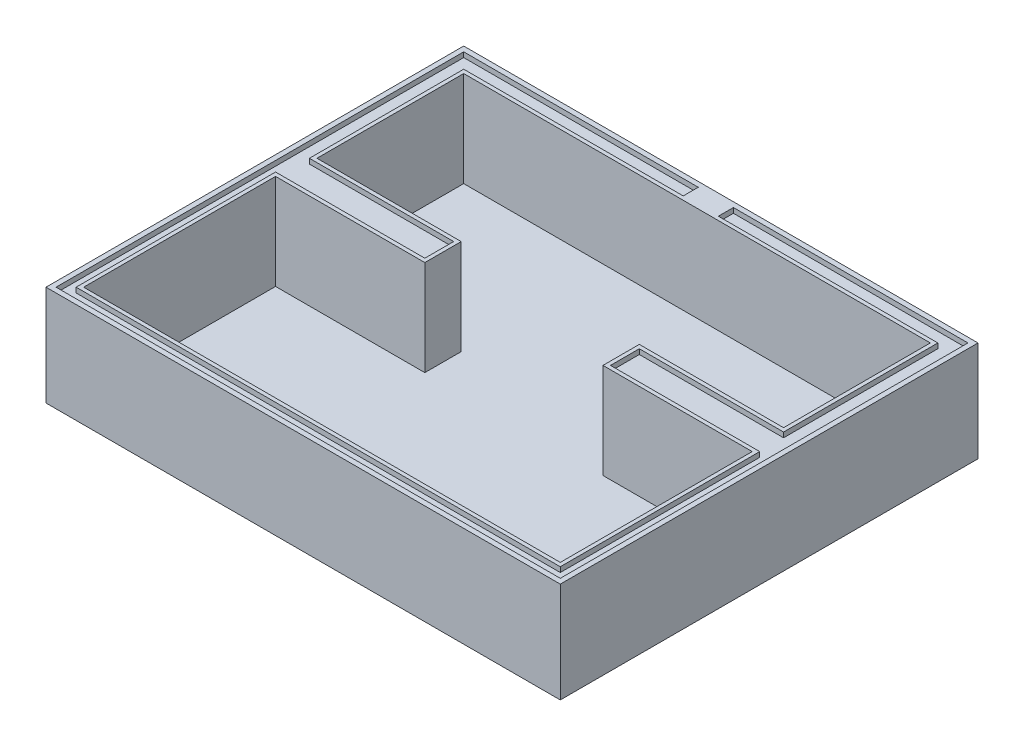
SolidWorks part; units mm, degrees
ref_plane "Front Plane" through (0, 0, 0) normal (0, 0, 1) x (1, 0, 0)
ref_plane "Top Plane" through (0, 0, 0) normal (0, 1, 0) x (1, 0, 0)
ref_plane "Right Plane" through (0, 0, 0) normal (1, 0, 0) x (0, 0, -1)
sketch "Sketch1" plane through (0, 0, 0) normal (0, 1, 0) x (1, 0, 0)
  line L1 (102.5, 83.25) -> (-102.5, 83.25)
  line L2 (102.5, 83.25) -> (102.5, -83.25)
  line L3 (102.5, -83.25) -> (-102.5, -83.25)
  line L4 (-102.5, 83.25) -> (-102.5, -83.25)
  line L5 (102.5, 83.25) -> (-102.5, -83.25) construction
  line L6 (102.5, -83.25) -> (-102.5, 83.25) construction
  point P0 (0, 0)
  dimension "D1" = 166.5
  dimension "D2" = 205
extrude "Boss-Extrude1" add sketch "Sketch1" along normal mid plane 40
sketch "Sketch3" plane through (0, 20, 0) normal (0, 1, 0) x (1, 0, 0)
  line L0 (-37.5, 13.25) -> (-37.5, 5.75) construction
  line L1 (-37.5, 5.75) -> (-100, 5.75) construction
  line L2 (-100, 5.75) -> (-100, 80.75) construction
  line L3 (-100, 80.75) -> (-7.5, 80.75) construction
  line L4 (-7.5, 80.75) -> (-7.5, 75.75) construction
  line L5 (-7.5, 75.75) -> (-95, 75.75) construction
  line L6 (-95, 75.75) -> (-95, 13.25) construction
  line L7 (-95, 13.25) -> (-37.5, 13.25) construction
  line L8 (-100, 5.75) -> (-37.5, 5.75) construction
  line L9 (-37.5, 5.75) -> (-37.5, 2.75) construction
  line L10 (-37.5, 2.75) -> (-97, 2.75) construction
  line L11 (-97, 2.75) -> (-97, -77.75) construction
  line L12 (-97, -77.75) -> (97, -77.75) construction
  line L13 (97, -77.75) -> (97, 2.75) construction
  line L14 (97, 2.75) -> (37.5, 2.75) construction
  line L15 (37.5, 2.75) -> (37.5, 5.75) construction
  line L16 (37.5, 5.75) -> (100, 5.75) construction
  line L17 (100, 5.75) -> (100, -80.75) construction
  line L18 (100, -80.75) -> (-100, -80.75) construction
  line L19 (-100, -80.75) -> (-100, 5.75) construction
  line L20 (37.5, 5.75) -> (37.5, 13.25) construction
  line L21 (37.5, 13.25) -> (95, 13.25) construction
  line L22 (95, 13.25) -> (95, 75.75) construction
  line L23 (95, 75.75) -> (7.5, 75.75) construction
  line L24 (7.5, 75.75) -> (7.5, 80.75) construction
  line L25 (7.5, 80.75) -> (100, 80.75) construction
  line L26 (100, 80.75) -> (100, 5.75) construction
  line L27 (100, 5.75) -> (37.5, 5.75) construction
  line L28 (-37.5, 13.25) -> (-37.5, 5.75)
  line L29 (-37.5, 5.75) -> (-100, 5.75)
  line L30 (-100, 5.75) -> (-100, 80.75)
  line L31 (-100, 80.75) -> (-7.5, 80.75)
  line L32 (-7.5, 80.75) -> (-7.5, 75.75)
  line L33 (-7.5, 75.75) -> (-95, 75.75)
  line L34 (-95, 75.75) -> (-95, 13.25)
  line L35 (-95, 13.25) -> (-37.5, 13.25)
  line L36 (-100, 5.75) -> (-37.5, 5.75)
  line L37 (-37.5, 5.75) -> (-37.5, 2.75)
  line L38 (-37.5, 2.75) -> (-97, 2.75)
  line L39 (-97, 2.75) -> (-97, -77.75)
  line L40 (-97, -77.75) -> (97, -77.75)
  line L41 (97, -77.75) -> (97, 2.75)
  line L42 (97, 2.75) -> (37.5, 2.75)
  line L43 (37.5, 2.75) -> (37.5, 5.75)
  line L44 (37.5, 5.75) -> (100, 5.75)
  line L45 (100, 5.75) -> (100, -80.75)
  line L46 (100, -80.75) -> (-100, -80.75)
  line L47 (-100, -80.75) -> (-100, 5.75)
  line L48 (37.5, 5.75) -> (37.5, 13.25)
  line L49 (37.5, 13.25) -> (95, 13.25)
  line L50 (95, 13.25) -> (95, 75.75)
  line L51 (95, 75.75) -> (7.5, 75.75)
  line L52 (7.5, 75.75) -> (7.5, 80.75)
  line L53 (7.5, 80.75) -> (100, 80.75)
  line L54 (100, 80.75) -> (100, 5.75)
  line L55 (100, 5.75) -> (37.5, 5.75)
  line L56 (-100.5, 5.75) -> (-100.5, 81.25)
  line L57 (-100.5, 81.25) -> (-7, 81.25)
  line L58 (-7, 81.25) -> (-7, 75.25)
  line L59 (-7, 75.25) -> (-94.5, 75.25)
  line L60 (-94.5, 75.25) -> (-94.5, 13.75)
  line L61 (-94.5, 13.75) -> (-37, 13.75)
  line L62 (-37, 13.75) -> (-37, 5.75)
  line L63 (37, 5.75) -> (37, 13.75)
  line L64 (37, 13.75) -> (94.5, 13.75)
  line L65 (94.5, 13.75) -> (94.5, 75.25)
  line L66 (94.5, 75.25) -> (7, 75.25)
  line L67 (7, 75.25) -> (7, 81.25)
  line L68 (7, 81.25) -> (100.5, 81.25)
  line L69 (100.5, 81.25) -> (100.5, 5.75)
  line L70 (-37, 5.75) -> (-37, 2.25)
  line L71 (-37, 2.25) -> (-96.5, 2.25)
  line L72 (-96.5, 2.25) -> (-96.5, -77.25)
  line L73 (-96.5, -77.25) -> (96.5, -77.25)
  line L74 (96.5, -77.25) -> (96.5, 2.25)
  line L75 (96.5, 2.25) -> (37, 2.25)
  line L76 (37, 2.25) -> (37, 5.75)
  line L77 (100.5, 5.75) -> (100.5, -81.25)
  line L78 (100.5, -81.25) -> (-100.5, -81.25)
  line L79 (-100.5, -81.25) -> (-100.5, 5.75)
  dimension "D1" = 0.5
extrude "Cut-Extrude1" cut sketch "Sketch3" against normal blind 2 contours L35 L34 L33 L32 L31 L30 L29 L28 | L47 L46 L45 L44 L43 L42 L41 L40 L39 L38 L37 L29 | L79 L78 L77 L69 L68 L67 L66 L65 L64 L63 L76 L75 L74 L73 L72 L71 L70 L62 L61 L60 L59 L58 L57 L56 L53 L54 L45 L46 L47 L30 L31 L32 L33 L34 L35 L28 L37 L38 L39 L40 L41 L42 L43 L48 L49 L50 L51 L52 | L54 L53 L52 L51 L50 L49 L48 L44
sketch "Sketch5" plane through (0, 20, 0) normal (0, 1, 0) x (1, 0, 0)
  line L0 (-94.5, 13.75) -> (-37, 13.75) construction
  line L1 (-37, 13.75) -> (-37, 2.25) construction
  line L2 (-37, 2.25) -> (-96.5, 2.25) construction
  line L3 (-96.5, 2.25) -> (-96.5, -77.25) construction
  line L4 (-96.5, -77.25) -> (96.5, -77.25) construction
  line L5 (96.5, -77.25) -> (96.5, 2.25) construction
  line L6 (96.5, 2.25) -> (37, 2.25) construction
  line L7 (37, 2.25) -> (37, 13.75) construction
  line L8 (37, 13.75) -> (94.5, 13.75) construction
  line L9 (94.5, 13.75) -> (94.5, 75.25) construction
  line L10 (94.5, 75.25) -> (7, 75.25) construction
  line L11 (-7, 75.25) -> (-94.5, 75.25) construction
  line L12 (-94.5, 75.25) -> (-94.5, 13.75) construction
  line L13 (-94.5, 13.75) -> (-37, 13.75)
  line L14 (-37, 13.75) -> (-37, 2.25)
  line L15 (-37, 2.25) -> (-96.5, 2.25)
  line L16 (-96.5, 2.25) -> (-96.5, -77.25)
  line L17 (-96.5, -77.25) -> (96.5, -77.25)
  line L18 (96.5, -77.25) -> (96.5, 2.25)
  line L19 (96.5, 2.25) -> (37, 2.25)
  line L20 (37, 2.25) -> (37, 13.75)
  line L21 (37, 13.75) -> (94.5, 13.75)
  line L22 (94.5, 13.75) -> (94.5, 75.25)
  line L23 (94.5, 75.25) -> (7, 75.25)
  line L24 (-7, 75.25) -> (-94.5, 75.25)
  line L25 (-94.5, 75.25) -> (-94.5, 13.75)
  line L26 (-7, 75.25) -> (7, 75.25)
  line L27 (-93, 73.75) -> (-93, 15.25)
  line L28 (-93, 15.25) -> (-35.5, 15.25)
  line L29 (-35.5, 15.25) -> (-35.5, 0.75)
  line L30 (-35.5, 0.75) -> (-95, 0.75)
  line L31 (-95, 0.75) -> (-95, -75.75)
  line L32 (-95, -75.75) -> (95, -75.75)
  line L33 (95, -75.75) -> (95, 0.75)
  line L34 (95, 0.75) -> (35.5, 0.75)
  line L35 (35.5, 0.75) -> (35.5, 15.25)
  line L36 (35.5, 15.25) -> (93, 15.25)
  line L37 (93, 15.25) -> (93, 73.75)
  line L38 (93, 73.75) -> (7, 73.75)
  line L39 (-7, 73.75) -> (7, 73.75)
  line L40 (-7, 73.75) -> (-93, 73.75)
  dimension "D1" = 1.5
extrude "Cut-Extrude3" cut sketch "Sketch5" against normal offset from surface (38 mm away) 2 contours L39 L40 L27 L28 L29 L30 L31 L32 L33 L34 L35 L36 L37 L38 up to face at (0, -20, 0)
